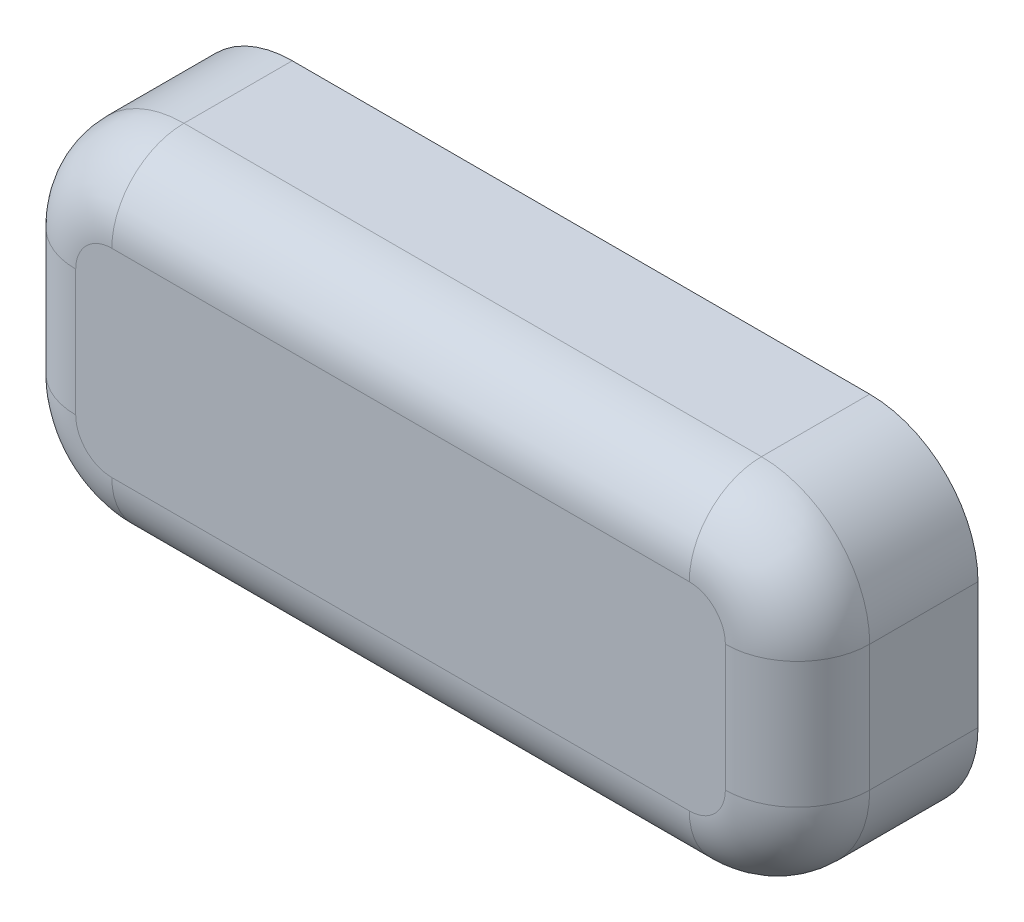
SolidWorks part; units mm, degrees
ref_plane "Front Plane" through (0, 0, 0) normal (0, 0, 1) x (1, 0, 0)
ref_plane "Top Plane" through (0, 0, 0) normal (0, 1, 0) x (1, 0, 0)
ref_plane "Right Plane" through (0, 0, 0) normal (1, 0, 0) x (0, 0, -1)
sketch "Sketch1" plane through (0, 0, 0) normal (0, 0, 1) x (1, 0, 0)
  line L1 (0, 0) -> (220, 0)
  line L2 (0, 0) -> (0, -95)
  line L3 (0, -95) -> (220, -95)
  line L4 (220, 0) -> (220, -95)
  dimension "D1" = 95
  dimension "D2" = 220
extrude "Boss-Extrude1" add sketch "Sketch1" along normal blind 50
fillet "Fillet1" radius 30 4 edges at (220, -95, 25) (220, 0, 25) (0, -95, 25) (0, 0, 25)
fillet "Fillet2" radius 20 8 edges at (8.7868, -86.2132, 50) (0, -47.5, 50) (8.7868, -8.7868, 50) (110, 0, 50) (211.2132, -8.7868, 50) (220, -47.5, 50) (211.2132, -86.2132, 50) (110, -95, 50)
shell "Shell1" thickness 1.5
